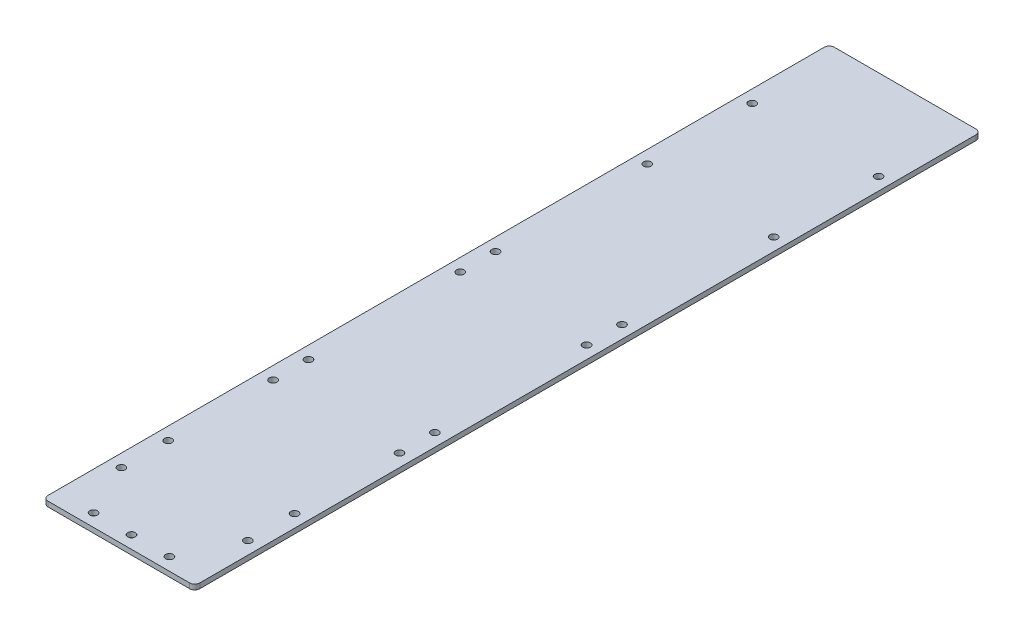
SolidWorks part; units mm, degrees
ref_plane "Спереди" through (0, 0, 0) normal (0, 0, 1) x (1, 0, 0)
ref_plane "Сверху" through (0, 0, 0) normal (0, 1, 0) x (1, 0, 0)
ref_plane "Справа" through (0, 0, 0) normal (1, 0, 0) x (0, 0, -1)
sketch "компоновка" plane through (0, 0, 0) normal (0, 1, 0) x (1, 0, 0)
  line L0 (0, -113.5) -> (0, -44.5) construction
  line L1 (-29, -113.5) -> (29, -113.5) construction
  line L2 (-29, -113.5) -> (-29, -44.5) construction
  line L3 (-29, -44.5) -> (29, -44.5) construction
  line L4 (29, -113.5) -> (29, -44.5) construction
  line L5 (-25, -109) -> (25, -109) construction
  line L6 (-25, -109) -> (-25, -49) construction
  line L7 (-25, -49) -> (25, -49) construction
  line L8 (25, -109) -> (25, -49) construction
  line L9 (-25, -49) -> (25, -109) construction
  line L10 (-29, -79) -> (29, -79) construction
  line L11 (0, -39.5) -> (0, 29.5) construction
  line L12 (-29, -39.5) -> (29, -39.5) construction
  line L13 (-29, -39.5) -> (-29, 29.5) construction
  line L14 (-29, 29.5) -> (29, 29.5) construction
  line L15 (29, -39.5) -> (29, 29.5) construction
  line L16 (-25, -35) -> (25, -35) construction
  line L17 (-25, -35) -> (-25, 25) construction
  line L18 (-25, 25) -> (25, 25) construction
  line L19 (25, -35) -> (25, 25) construction
  line L20 (-25, 25) -> (25, -35) construction
  line L21 (-29, -5) -> (29, -5) construction
  line L22 (0, 34.5) -> (0, 103.5) construction
  line L23 (-29, 34.5) -> (29, 34.5) construction
  line L24 (-29, 34.5) -> (-29, 103.5) construction
  line L25 (-29, 103.5) -> (29, 103.5) construction
  line L26 (29, 34.5) -> (29, 103.5) construction
  line L27 (-25, 39) -> (25, 39) construction
  line L28 (-25, 39) -> (-25, 99) construction
  line L29 (-25, 99) -> (25, 99) construction
  line L30 (25, 39) -> (25, 99) construction
  line L31 (-25, 99) -> (25, 39) construction
  line L32 (-29, 69) -> (29, 69) construction
  circle A0 centre (-25, -109) radius 1.5 construction
  circle A1 centre (25, -109) radius 1.5 construction
  circle A2 centre (25, -49) radius 1.5 construction
  circle A3 centre (-25, -49) radius 1.5 construction
  circle A4 centre (-25, -35) radius 1.5 construction
  circle A5 centre (25, -35) radius 1.5 construction
  circle A6 centre (25, 25) radius 1.5 construction
  circle A7 centre (-25, 25) radius 1.5 construction
  circle A8 centre (-25, 39) radius 1.5 construction
  circle A9 centre (25, 39) radius 1.5 construction
  circle A10 centre (25, 99) radius 1.5 construction
  circle A11 centre (-25, 99) radius 1.5 construction
  point P10 (0, -79)
  point P11 (0, -79)
  point P31 (0, -5)
  point P32 (0, -5)
  point P49 (0, 69)
  point P50 (0, 69)
  dimension "D5" = 3
  dimension "D2" = 50
  dimension "D3" = 60
  dimension "D4" = 69
  dimension "D6" = 5
  dimension "D7" = 5
  dimension "D8" = 5
sketch "эскиз 1" plane through (0, 0, 0) normal (0, 1, 0) x (1, 0, 0)
  line L0 (0, -135) -> (0, 176) construction
  line L1 (-30, -135) -> (30, -135)
  line L2 (-30, -135) -> (-30, 176)
  line L3 (-30, 176) -> (30, 176)
  line L4 (30, -135) -> (30, 176)
  line L6 (-30, 0) -> (30, 0) construction
  dimension "D1" = 60
  dimension "D2" = 176
  dimension "D3" = 135
extrude "тело" add sketch "эскиз 1" along normal blind 2
sketch "Эскиз5" plane through (0, 2, 0) normal (0, 1, 0) x (1, 0, 0)
  circle A0 centre (-25, 99) radius 1.5
  circle A1 centre (25, 99) radius 1.5
  circle A2 centre (25, 39) radius 1.5
  circle A3 centre (-25, 39) radius 1.5
  circle A4 centre (-25, 25) radius 1.5
  circle A5 centre (25, 25) radius 1.5
  circle A6 centre (-25, -35) radius 1.5
  circle A7 centre (25, -35) radius 1.5
  circle A8 centre (25, -49) radius 1.5
  circle A9 centre (-25, -49) radius 1.5
  circle A10 centre (25, -109) radius 1.5
  circle A11 centre (-25, -109) radius 1.5
  dimension "D1" = 3
extrude "крепления плат" cut sketch "Эскиз5" against normal through all
sketch "эскиз 3" plane through (0, 2, 0) normal (0, 1, 0) x (1, 0, 0)
  line L0 (0, 176) -> (0, -135) construction
  line L1 (30, 176) -> (-30, 176) construction
  line L2 (-30, -135) -> (30, -135) construction
  line L3 (-30, 20.5) -> (30, 20.5) construction
  line L6 (-25, 140.5) -> (25, 140.5) construction
  line L7 (-25, -90.5) -> (25, -90.5) construction
  line L8 (-30, 176) -> (-30, -135) construction
  line L9 (30, -135) -> (30, 176) construction
  circle A0 centre (-25, -90.5) radius 1.5
  circle A1 centre (25, -90.5) radius 1.5
  circle A2 centre (-25, 140.5) radius 1.5
  circle A3 centre (25, 140.5) radius 1.5
  point P2 (0, -90.5)
  point P5 (0, 140.5)
  dimension "D1" = 3
  dimension "D2" = 50
  dimension "D3" = 120
  dimension "D4" = 111
extrude "стойки между этажами" cut sketch "эскиз 3" against normal through all
sketch "Эскиз8" plane through (0, 2, 0) normal (0, 1, 0) x (1, 0, 0)
  line L0 (0, 176) -> (0, -135) construction
  line L1 (30, 176) -> (-30, 176) construction
  line L2 (-30, -135) -> (30, -135) construction
  line L3 (-15, -130) -> (15, -130) construction
  circle A0 centre (-15, -130) radius 1.5
  circle A1 centre (15, -130) radius 1.5
  circle A2 centre (0, -130) radius 1.5
  point P10 (0, -130)
  dimension "D1" = 3
  dimension "D2" = 30
  dimension "D3" = 130
extrude "крепление камеры для линии" cut sketch "Эскиз8" against normal through all
fillet "Скругление1" radius 2 4 edges at (-30, 1, 135) (30, 1, 135) (30, 1, -176) (-30, 1, -176)
